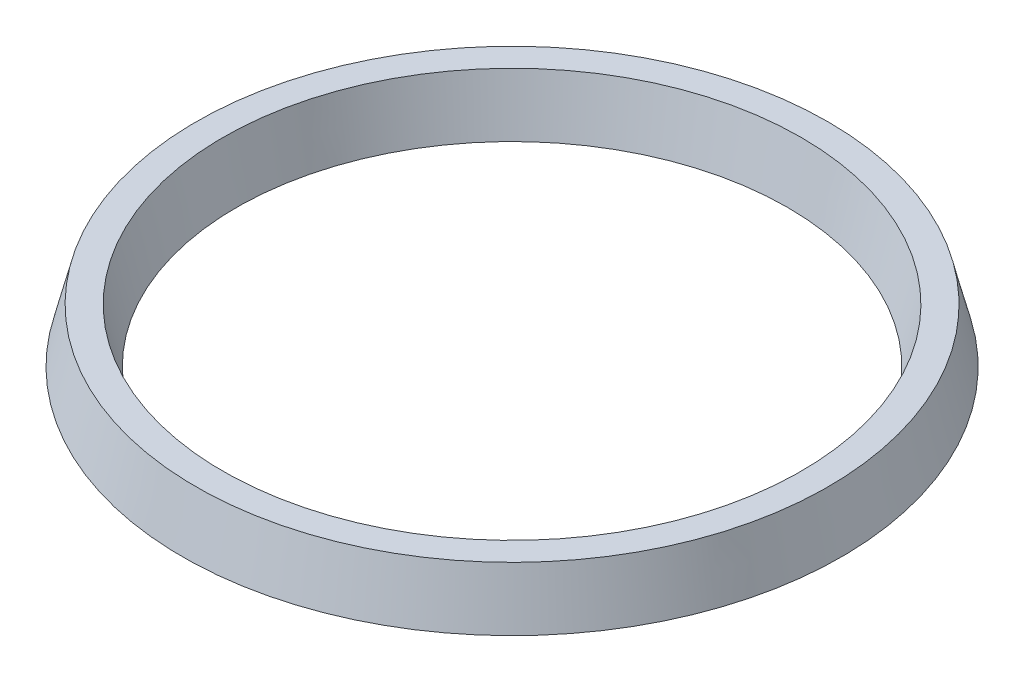
SolidWorks part; units mm, degrees
ref_plane "Front Plane" through (0, 0, 0) normal (0, 0, 1) x (1, 0, 0)
ref_plane "Top Plane" through (0, 0, 0) normal (0, 1, 0) x (1, 0, 0)
ref_plane "Right Plane" through (0, 0, 0) normal (1, 0, 0) x (0, 0, -1)
sketch "Sketch1" plane through (0, 0, 0) normal (0, 0, 1) x (1, 0, 0)
  line L0 (0, 78.0502) -> (0, 0) construction
  line L1 (0, 0) -> (-67.31, 0) construction
  line L2 (-67.31, 0) -> (-67.31, 78.0502) construction
  line L3 (3, 6) -> (-3, 6)
  line L4 (-3, 6) -> (-6, -6)
  line L5 (-6, -6) -> (-3, -6)
  line L6 (-3, -6) -> (-1.8638, -1.4552)
  line L7 (1.8638, -1.4552) -> (3, -6)
  line L8 (3, -6) -> (6, -6)
  line L9 (6, -6) -> (3, 6)
  arc A0 (-1.8638, -1.4552) -> (1.8638, -1.4552) centre (0, -1.9212) cw
  point P12 (0, 0)
  dimension "D1" = 6
  dimension "D2" = 12
  dimension "D3" = 3
  dimension "D4" = 12
  dimension "D5" = 6
  dimension "D6" = 6
  dimension "D7" = 3
  dimension "D8" = 67.31
revolve "Revolve1" add sketch "Sketch1" angle 360 about L2
